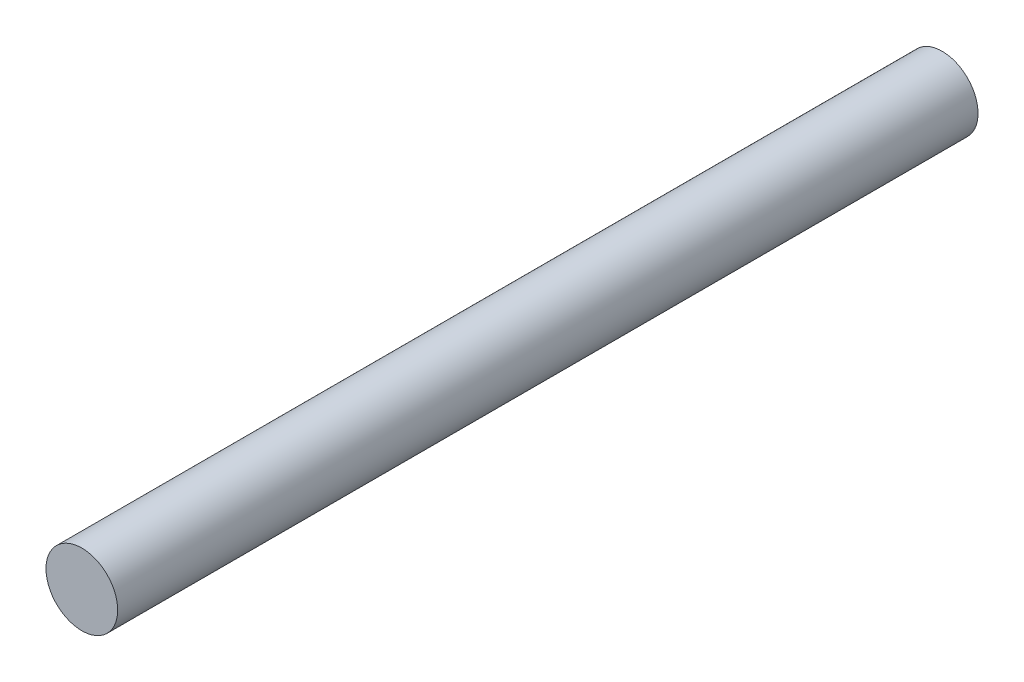
SolidWorks part; units mm, degrees
ref_plane "Front Plane" through (0, 0, 0) normal (0, 0, 1) x (1, 0, 0)
ref_plane "Top Plane" through (0, 0, 0) normal (0, 1, 0) x (1, 0, 0)
ref_plane "Right Plane" through (0, 0, 0) normal (1, 0, 0) x (0, 0, -1)
sketch "Sketch1" plane through (0, 0, 0) normal (0, 0, 1) x (1, 0, 0)
  circle A0 centre (0, 0) radius 1.5875
  dimension "D1" = 3.175
extrude "Boss-Extrude1" add sketch "Sketch1" along normal mid plane 38.1
